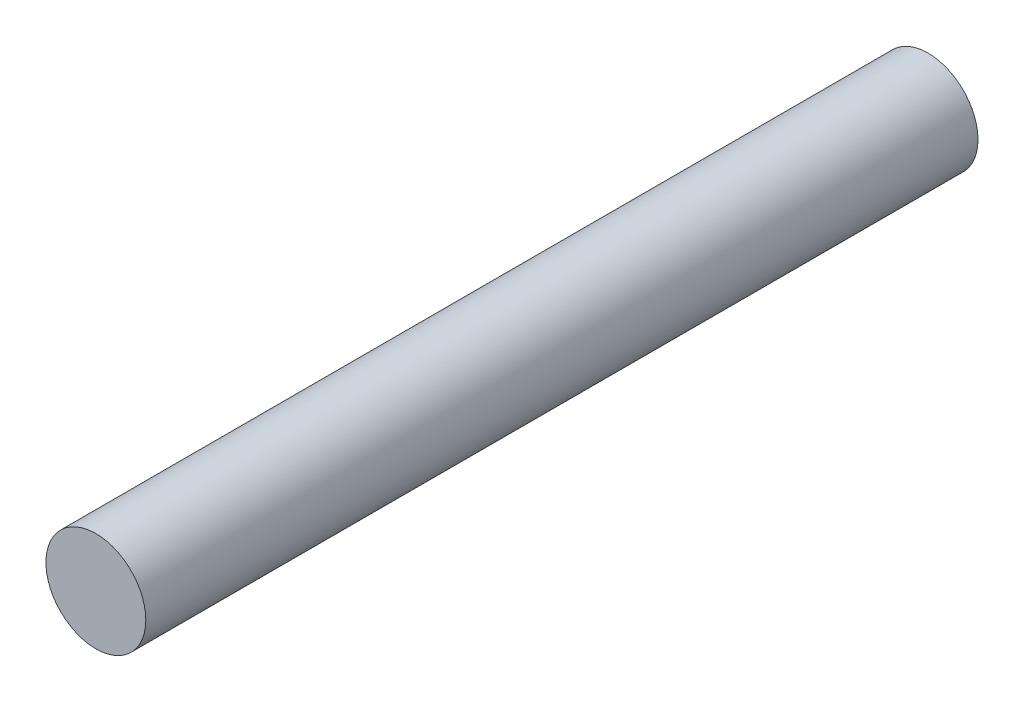
SolidWorks part; units mm, degrees
ref_plane "Спереди" through (0, 0, 0) normal (0, 0, 1) x (1, 0, 0)
ref_plane "Сверху" through (0, 0, 0) normal (0, 1, 0) x (1, 0, 0)
ref_plane "Справа" through (0, 0, 0) normal (1, 0, 0) x (0, 0, -1)
sketch "Эскиз1" plane through (0, 0, 0) normal (0, 0, 1) x (1, 0, 0)
  circle A0 centre (0, 0) radius 1.5
  dimension "D1" = 3
extrude "Вытянуть1" add sketch "Эскиз1" along normal blind 25
